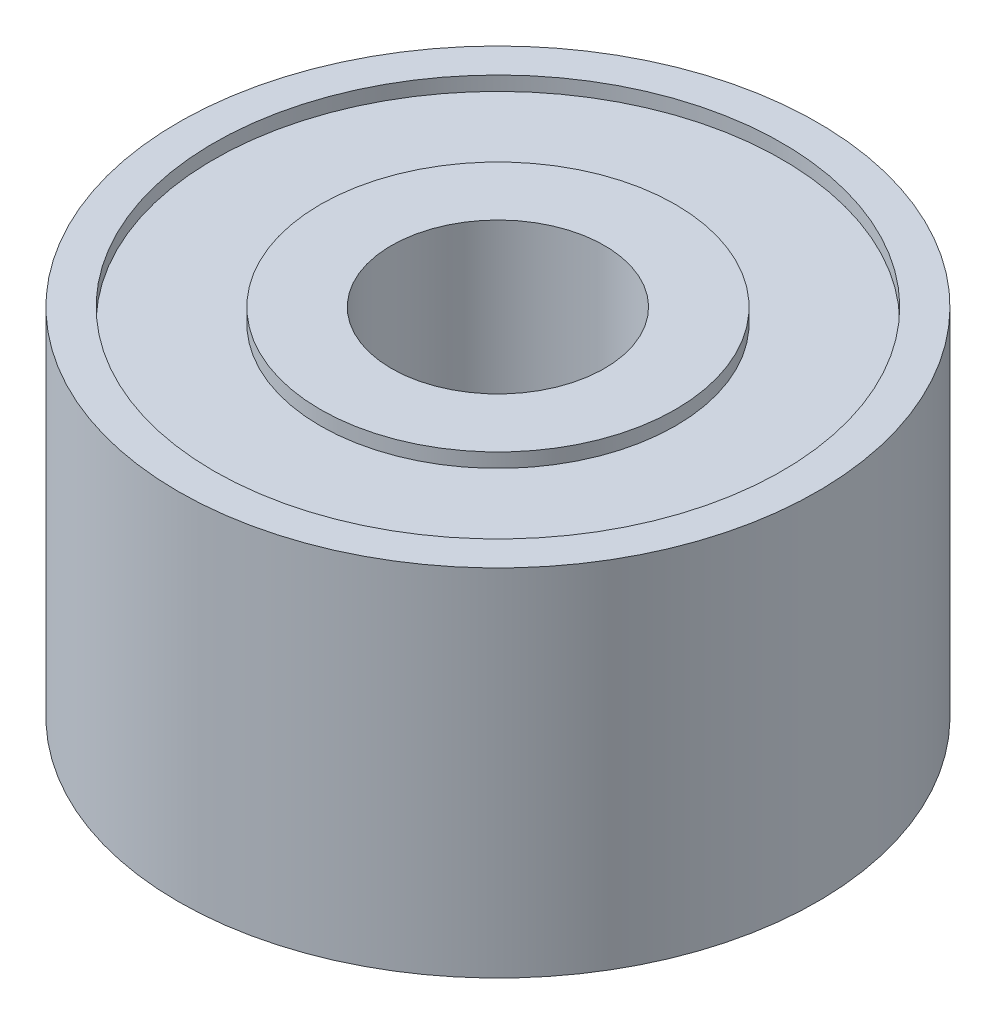
SolidWorks part; units mm, degrees
ref_plane "前视基准面" through (0, 0, 0) normal (0, 0, 1) x (1, 0, 0)
ref_plane "上视基准面" through (0, 0, 0) normal (0, 1, 0) x (1, 0, 0)
ref_plane "右视基准面" through (0, 0, 0) normal (1, 0, 0) x (0, 0, -1)
sketch "草图1" plane through (0, 0, 0) normal (0, 1, 0) x (1, 0, 0)
  circle A0 centre (0, 0) radius 1.5
  circle A1 centre (0, 0) radius 4.5
  dimension "D1" = 3
  dimension "D2" = 9
extrude "凸台-拉伸1" add sketch "草图1" along normal blind 5
sketch "草图2" plane through (0, 5, 0) normal (0, 1, 0) x (1, 0, 0)
  circle A0 centre (0, 0) radius 2.5
  circle A2 centre (0, 0) radius 1.5 construction
  circle A3 centre (0, 0) radius 4
  circle A4 centre (0, 0) radius 4.5 construction
  dimension "D1" = 1
  dimension "D2" = 0.5
extrude "切除-拉伸1" cut sketch "草图2" against normal blind 0.2
sketch "草图3" plane through (0, 0, 0) normal (0, -1, 0) x (1, 0, 0)
  circle A0 centre (0, 0) radius 2.5
  circle A1 centre (0, 0) radius 1.5 construction
  circle A2 centre (0, 0) radius 4
  circle A3 centre (0, 0) radius 4.5 construction
  dimension "D1" = 1
  dimension "D2" = 0.5
extrude "切除-拉伸2" cut sketch "草图3" against normal blind 0.2
